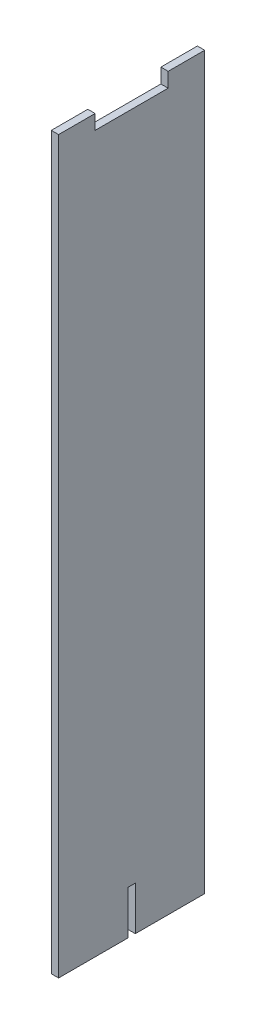
SolidWorks part; units mm, degrees
ref_plane "Front" through (0, 0, 0) normal (0, 0, 1) x (1, 0, 0)
ref_plane "Top" through (0, 0, 0) normal (0, 1, 0) x (1, 0, 0)
ref_plane "Right" through (0, 0, 0) normal (1, 0, 0) x (0, 0, -1)
sketch "Sketch1" plane through (0, 0, 0) normal (1, 0, 0) x (0, 0, -1)
  line L0 (0, 17.5824) -> (0, -983.7363) construction
  line L1 (100, 16.2637) -> (-100, 16.2637)
  line L2 (-100, 16.2637) -> (-100, -983.7363)
  line L3 (-100, -983.7363) -> (-5, -983.7363)
  line L4 (-5, -983.7363) -> (-5, -923.7363)
  line L5 (-5, -923.7363) -> (5, -923.7363)
  line L6 (5, -983.7363) -> (5, -923.7363)
  line L7 (100, -983.7363) -> (5, -983.7363)
  line L8 (100, 16.2637) -> (100, -983.7363)
  point P10 (0, -923.7363)
  point P13 (0, 16.2637)
  dimension "D1" = 100
  dimension "D2" = 1000
  dimension "D3" = 5
  dimension "D4" = 60
  dimension "D5" = 16.2637
extrude "Boss-Extrude1" add sketch "Sketch1" along normal blind 10
sketch "Sketch2" plane through (0, 0, 0) normal (-1, 0, 0) x (0, 0, 1)
  line L0 (-50, 16.2637) -> (-50, -3.7363)
  line L1 (-100, 16.2637) -> (100, 16.2637) construction
  line L2 (-50, -3.7363) -> (50, -3.7363)
  line L3 (50, -3.7363) -> (50, 16.2637)
  line L4 (50, 16.2637) -> (-50, 16.2637)
  dimension "D1" = 100
  dimension "D2" = 20
  dimension "D3" = 50
extrude "Cut-Extrude1" cut sketch "Sketch2" against normal blind 10
